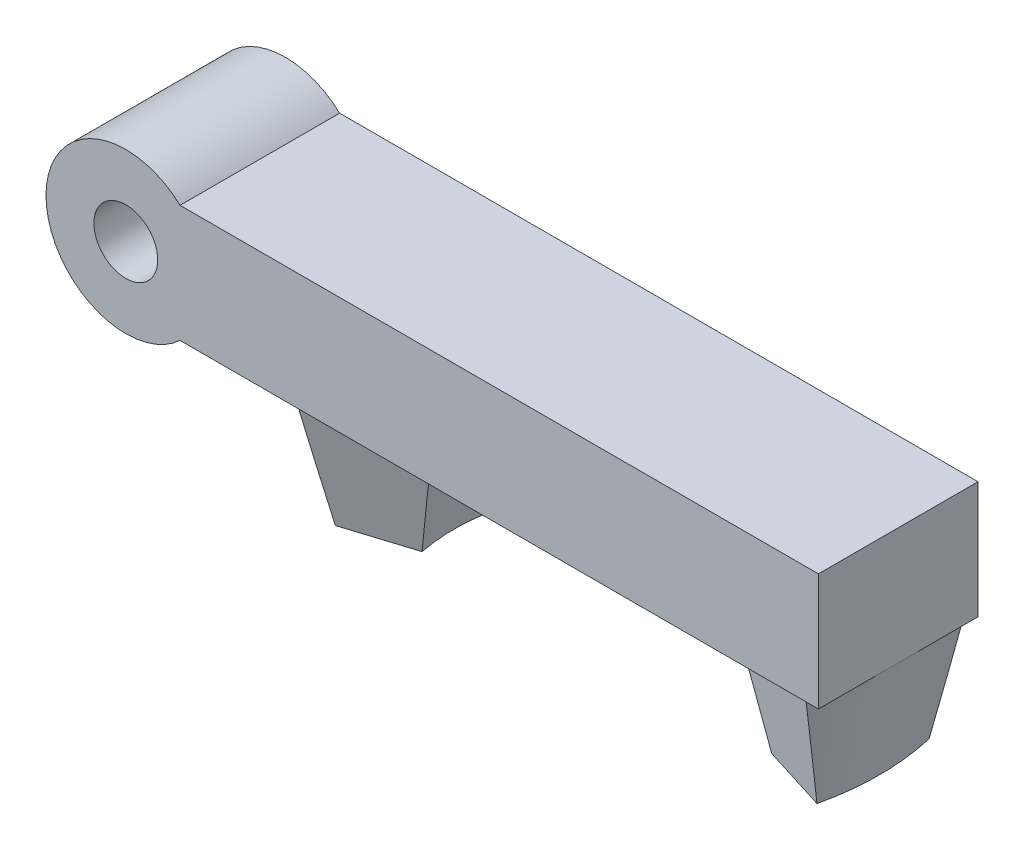
SolidWorks part; units mm, degrees
ref_plane "Front Plane" through (0, 0, 0) normal (0, 0, 1) x (1, 0, 0)
ref_plane "Top Plane" through (0, 0, 0) normal (0, 1, 0) x (1, 0, 0)
ref_plane "Right Plane" through (0, 0, 0) normal (1, 0, 0) x (0, 0, -1)
sketch "Sketch1" plane through (0, 0, 0) normal (0, 0, 1) x (1, 0, 0)
  line L0 (32.5495, -2.75) -> (31.6679, -7.75) construction
  line L1 (2.5495, 2.75) -> (32.5495, 2.75)
  line L2 (2.5495, 2.75) -> (2.5495, -2.75) construction
  line L3 (2.5495, -2.75) -> (32.5495, -2.75) construction
  line L4 (32.5495, 2.75) -> (32.5495, -2.75)
  line L5 (31.6679, -7.75) -> (28.9311, -7.75) construction
  line L6 (30.2995, -7.75) -> (30.2995, -2.75) construction
  line L7 (31.6679, -7.75) -> (31.6679, -2.75) construction
  line L8 (28.0495, -2.75) -> (28.9311, -7.75) construction
  line L9 (26.5495, -2.75) -> (25.6679, -7.75) construction
  line L10 (25.6679, -7.75) -> (22.9311, -7.75) construction
  line L11 (22.0495, -2.75) -> (22.9311, -7.75) construction
  line L12 (28.0495, -2.75) -> (26.5495, -2.75) construction
  line L13 (22.0495, -2.75) -> (2.5495, -2.75)
  line L14 (32.5495, -2.75) -> (22.0495, -2.75)
  circle A0 centre (0, 0) radius 3.75 construction
  arc A2 (2.5495, 2.75) -> (2.5495, -2.75) centre (0, 0) ccw
  circle A3 centre (0, 0) radius 1.5
  dimension "D1" = 7.5
  dimension "D2" = 3
  dimension "D3" = 5.5
  dimension "D4" = 30
  dimension "D5" = 10
  dimension "D6" = 4.5
  dimension "D7" = 5
  dimension "D9" = 1.5
  dimension "D8" = 2
extrude "Boss-Extrude1" add sketch "Sketch1" along normal blind 7.5
sketch "Sketch2" plane through (0, -2.75, 0) normal (0, -1, 0) x (1, 0, 0)
  line L0 (32.5495, 7.5) -> (32.5495, 0) construction
  line L1 (20.0495, 3.75) -> (31.9737, 7.5) construction
  line L2 (2.5495, 7.5) -> (32.5495, 7.5) construction
  line L3 (20.0495, 3.75) -> (32.5495, 3.75) construction
  line L4 (31.9737, 7.5) -> (27.2041, 6)
  line L5 (31.9737, 0) -> (27.2041, 1.5)
  line L6 (20.0495, 3.75) -> (20.0495, 0) construction
  line L7 (2.5495, 0) -> (32.5495, 0) construction
  line L8 (8.1253, 7.5) -> (12.895, 6)
  line L9 (8.1253, 0) -> (12.895, 1.5)
  circle A0 centre (20.0495, 3.75) radius 12.5 construction
  circle A1 centre (20.0495, 3.75) radius 7.5 construction
  arc A2 (31.9737, 7.5) -> (31.9737, 0) centre (20.0495, 3.75) cw
  arc A3 (27.2041, 1.5) -> (27.2041, 6) centre (20.0495, 3.75) ccw
  arc A4 (8.1253, 7.5) -> (8.1253, 0) centre (20.0495, 3.75) ccw
  arc A5 (12.895, 1.5) -> (12.895, 6) centre (20.0495, 3.75) cw
  point P5 (32.5495, 3.75)
  dimension "D1" = 25
  dimension "D2" = 5
extrude "Boss-Extrude3" add sketch "Sketch2" along normal blind 5 draft 10
